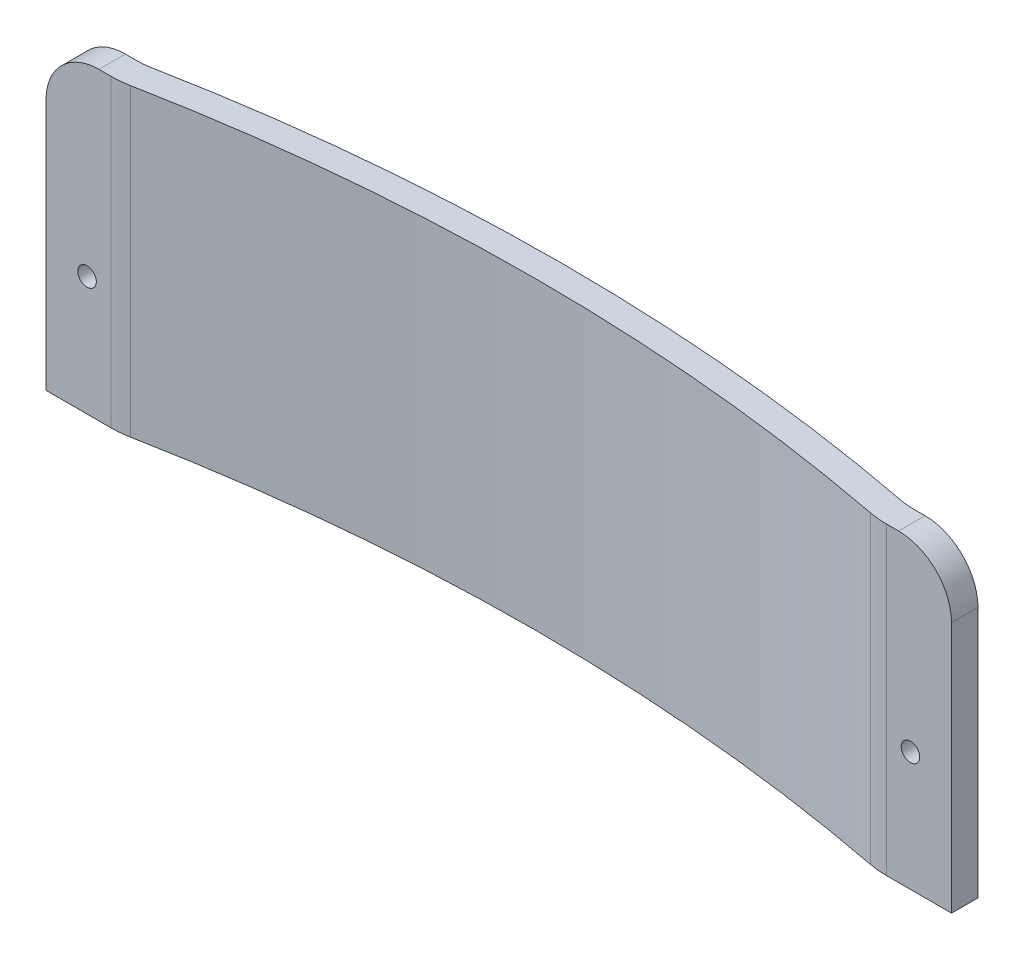
SolidWorks part; units mm, degrees
material "Белая сосна"
ref_plane "Спереди" through (0, 0, 0) normal (0, 0, 1) x (1, 0, 0)
ref_plane "Сверху" through (0, 0, 0) normal (0, 1, 0) x (1, 0, 0)
ref_plane "Справа" through (0, 0, 0) normal (1, 0, 0) x (0, 0, -1)
sketch "Эскиз1" plane through (0, 0, 0) normal (0, 1, 0) x (1, 0, 0)
  line L0 (0, 0) -> (0, 34.5697) construction
  line L1 (-171, 0) -> (-146.3833, 0)
  line L2 (171, 0) -> (146.3833, 0)
  arc A0 (-139.7554, 0.6333) -> (139.7554, 0.6333) centre (0, -724.0131) cw
  arc A1 (146.3833, 0) -> (139.7554, 0.6333) centre (146.3833, 35) cw
  arc A2 (-146.3833, 0) -> (-139.7554, 0.6333) centre (-146.3833, 35) ccw
  point P10 (143, 0)
  point P13 (-143, 0)
  dimension "D2" = 738
  dimension "D4" = 35
  dimension "D1" = 342
  dimension "D3" = 28
extrude "Вытянуть-Тонкостенный1" add sketch "Эскиз1" along normal blind 115 thin thin type one direction wall 10
sketch "Эскиз4" plane through (0, 0, 0) normal (0, 0, 1) x (1, 0, 0)
  line L0 (171, 115) -> (171, 0) construction
  line L1 (171, 0) -> (146.3833, 0) construction
  circle A0 centre (-155.5, 45) radius 3.5
  circle A1 centre (155.5, 45) radius 3.5
  dimension "D1" = 7
  dimension "D2" = 15.5
  dimension "D3" = 311
  dimension "D4" = 45
extrude "Вырез-Вытянуть2" cut sketch "Эскиз4" against normal through all
fillet "Скругление1" radius 20 2 edges at (-171, 115, -5) (171, 115, -5)
